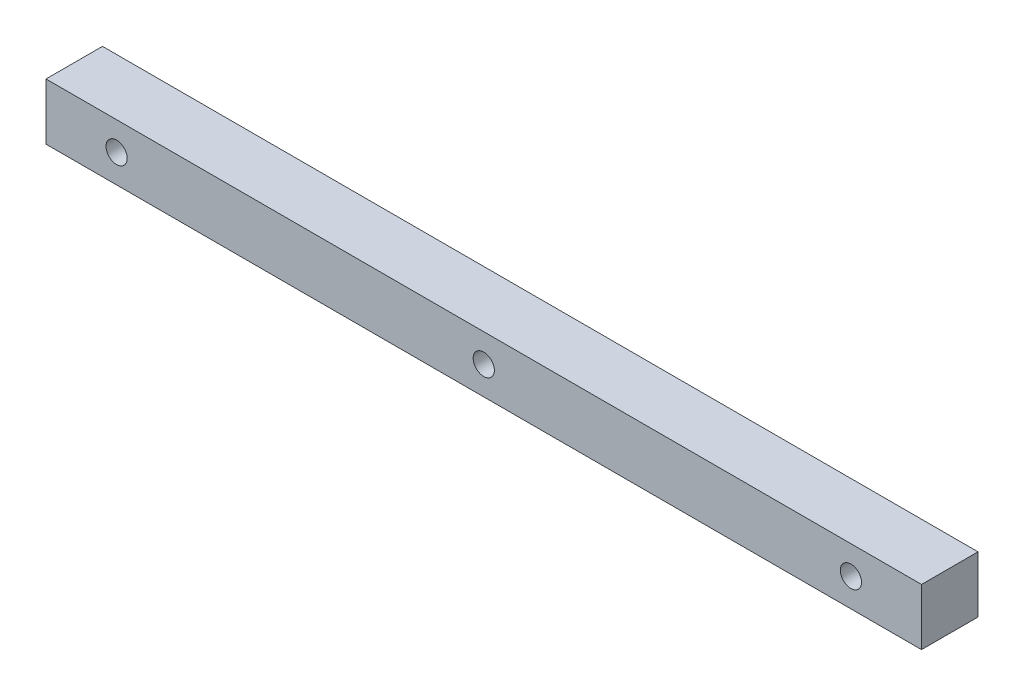
SolidWorks part; units mm, degrees
ref_plane "前视基准面" through (0, 0, 0) normal (0, 0, 1) x (1, 0, 0)
ref_plane "上视基准面" through (0, 0, 0) normal (0, 1, 0) x (1, 0, 0)
ref_plane "右视基准面" through (0, 0, 0) normal (1, 0, 0) x (0, 0, -1)
sketch "草图1" plane through (0, 0, 0) normal (0, 0, 1) x (1, 0, 0)
  line L0 (0, 4) -> (124, 4) construction
  line L1 (0, 0) -> (124, 0)
  line L2 (0, 0) -> (0, 8)
  line L3 (0, 8) -> (124, 8)
  line L4 (124, 0) -> (124, 8)
  line L5 (62, 8) -> (62, 0) construction
  circle A0 centre (62, 4) radius 1.5
  circle A1 centre (10, 4) radius 1.5
  circle A2 centre (114, 4) radius 1.5
  dimension "D3" = 3
  dimension "D4" = 3
  dimension "D1" = 124
  dimension "D2" = 8
  dimension "D5" = 52
extrude "凸台-拉伸1" add sketch "草图1" along normal blind 8
